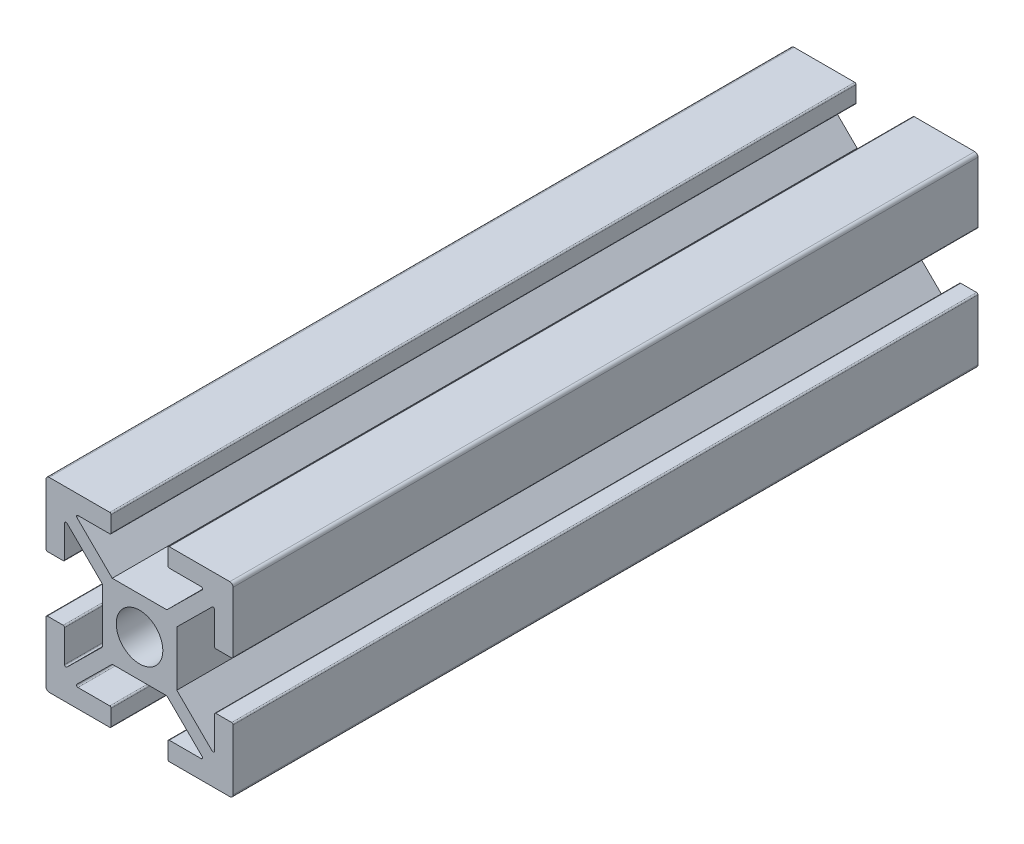
SolidWorks part; units mm, degrees
ref_plane "Front Plane" through (0, 0, 0) normal (0, 0, 1) x (1, 0, 0)
ref_plane "Top Plane" through (0, 0, 0) normal (0, 1, 0) x (1, 0, 0)
ref_plane "Right Plane" through (0, 0, 0) normal (1, 0, 0) x (0, 0, -1)
sketch "Sketch1" plane through (0, 0, 0) normal (0, 0, 1) x (1, 0, 0)
  line L0 (-31.3764, -0.0618) -> (-29.6764, -0.0618)
  line L1 (-24.6764, 6.9382) -> (-31.1764, 6.9382)
  line L2 (-31.5264, 0.0882) -> (-31.5264, 6.5882)
  line L3 (-18.5469, 0.9382) -> (-24.4133, 0.9382)
  line L4 (-25.4801, -6.0072) -> (-25.4801, -0.1164)
  line L5 (-29.5264, 0.0882) -> (-29.5264, 3.5244)
  line L6 (-28.0945, 4.9382) -> (-24.6764, 4.9382)
  line L7 (-24.5264, 5.0882) -> (-24.5264, 6.7882)
  line L8 (-29.5264, 4.9382) -> (-25.4801, 0.9382) construction
  line L9 (-29.271, 3.631) -> (-25.4801, -0.1164)
  line L10 (-28.1999, 4.6815) -> (-24.4133, 0.9382)
  line L11 (-13.4338, 4.9382) -> (-17.4801, 0.9382) construction
  line L12 (-21.4801, -3.0618) -> (-21.4801, 8.6268) construction
  line L13 (-21.4801, -3.0618) -> (-36.4642, -3.0618) construction
  line L14 (-14.7603, 4.6815) -> (-18.5469, 0.9382)
  line L15 (-13.6893, 3.631) -> (-17.4801, -0.1164)
  line L16 (-18.4338, 5.0882) -> (-18.4338, 6.7882)
  line L17 (-14.8657, 4.9382) -> (-18.2838, 4.9382)
  line L18 (-13.4338, 0.0882) -> (-13.4338, 3.5244)
  line L19 (-17.4801, -6.0072) -> (-17.4801, -0.1164)
  line L20 (-11.4338, 0.0882) -> (-11.4338, 6.5882)
  line L21 (-18.2838, 6.9382) -> (-11.7838, 6.9382)
  line L22 (-11.5838, -0.0618) -> (-13.2838, -0.0618)
  line L23 (-13.4338, -11.0618) -> (-17.4801, -7.0618) construction
  line L24 (-29.5264, -11.0618) -> (-25.4801, -7.0618) construction
  line L25 (-11.5838, -6.0618) -> (-13.2838, -6.0618)
  line L26 (-18.2838, -13.0618) -> (-11.7838, -13.0618)
  line L27 (-11.4338, -6.2118) -> (-11.4338, -12.7118)
  line L28 (-13.4338, -6.2118) -> (-13.4338, -9.648)
  line L29 (-14.8657, -11.0618) -> (-18.2838, -11.0618)
  line L30 (-18.4338, -11.2118) -> (-18.4338, -12.9118)
  line L31 (-13.6893, -9.7547) -> (-17.4801, -6.0072)
  line L32 (-14.7603, -10.8051) -> (-18.5469, -7.0618)
  line L33 (-28.1999, -10.8051) -> (-24.4133, -7.0618)
  line L34 (-29.271, -9.7547) -> (-25.4801, -6.0072)
  line L35 (-24.5264, -11.2118) -> (-24.5264, -12.9118)
  line L36 (-28.0945, -11.0618) -> (-24.6764, -11.0618)
  line L37 (-29.5264, -6.2118) -> (-29.5264, -9.648)
  line L38 (-18.5469, -7.0618) -> (-24.4133, -7.0618)
  line L39 (-31.5264, -6.2118) -> (-31.5264, -12.7118)
  line L40 (-24.6764, -13.0618) -> (-31.1764, -13.0618)
  line L41 (-31.3764, -6.0618) -> (-29.6764, -6.0618)
  circle A0 centre (-21.4801, -3.0618) radius 2.5
  arc A1 (-31.5264, 6.5882) -> (-31.1764, 6.9382) centre (-31.1764, 6.5882) cw
  arc A2 (-31.3764, -0.0618) -> (-31.5264, 0.0882) centre (-31.3764, 0.0882) cw
  arc A3 (-29.6764, -0.0618) -> (-29.5264, 0.0882) centre (-29.6764, 0.0882) ccw
  arc A4 (-24.6764, 6.9382) -> (-24.5264, 6.7882) centre (-24.6764, 6.7882) cw
  arc A5 (-24.6764, 4.9382) -> (-24.5264, 5.0882) centre (-24.6764, 5.0882) ccw
  arc A6 (-28.1999, 4.6815) -> (-28.0945, 4.9382) centre (-28.0945, 4.7882) cw
  arc A7 (-29.271, 3.631) -> (-29.5264, 3.5244) centre (-29.3764, 3.5244) ccw
  arc A8 (-13.6893, 3.631) -> (-13.4338, 3.5244) centre (-13.5838, 3.5244) cw
  arc A9 (-14.7603, 4.6815) -> (-14.8657, 4.9382) centre (-14.8657, 4.7882) ccw
  arc A10 (-18.2838, 4.9382) -> (-18.4338, 5.0882) centre (-18.2838, 5.0882) cw
  arc A11 (-18.2838, 6.9382) -> (-18.4338, 6.7882) centre (-18.2838, 6.7882) ccw
  arc A12 (-13.2838, -0.0618) -> (-13.4338, 0.0882) centre (-13.2838, 0.0882) cw
  arc A13 (-11.5838, -0.0618) -> (-11.4338, 0.0882) centre (-11.5838, 0.0882) ccw
  arc A14 (-11.4338, 6.5882) -> (-11.7838, 6.9382) centre (-11.7838, 6.5882) ccw
  arc A15 (-11.4338, -12.7118) -> (-11.7838, -13.0618) centre (-11.7838, -12.7118) cw
  arc A16 (-11.5838, -6.0618) -> (-11.4338, -6.2118) centre (-11.5838, -6.2118) cw
  arc A17 (-13.2838, -6.0618) -> (-13.4338, -6.2118) centre (-13.2838, -6.2118) ccw
  arc A18 (-18.2838, -13.0618) -> (-18.4338, -12.9118) centre (-18.2838, -12.9118) cw
  arc A19 (-18.2838, -11.0618) -> (-18.4338, -11.2118) centre (-18.2838, -11.2118) ccw
  arc A20 (-14.7603, -10.8051) -> (-14.8657, -11.0618) centre (-14.8657, -10.9118) cw
  arc A21 (-13.6893, -9.7547) -> (-13.4338, -9.648) centre (-13.5838, -9.648) ccw
  arc A22 (-29.271, -9.7547) -> (-29.5264, -9.648) centre (-29.3764, -9.648) cw
  arc A23 (-28.1999, -10.8051) -> (-28.0945, -11.0618) centre (-28.0945, -10.9118) ccw
  arc A24 (-24.6764, -11.0618) -> (-24.5264, -11.2118) centre (-24.6764, -11.2118) cw
  arc A25 (-24.6764, -13.0618) -> (-24.5264, -12.9118) centre (-24.6764, -12.9118) ccw
  arc A26 (-29.6764, -6.0618) -> (-29.5264, -6.2118) centre (-29.6764, -6.2118) cw
  arc A27 (-31.3764, -6.0618) -> (-31.5264, -6.2118) centre (-31.3764, -6.2118) ccw
  arc A28 (-31.5264, -12.7118) -> (-31.1764, -13.0618) centre (-31.1764, -12.7118) ccw
  point P27 (-18.4338, 4.9382)
  point P28 (-11.4338, -13.0618)
  point P47 (-17.4801, -3.0618)
  point P57 (-21.4801, 0.9382)
  point P59 (-18.4338, 6.9382)
  point P60 (-13.4338, -0.0618)
  point P61 (-11.4338, -0.0618)
  point P62 (-11.4338, 6.9382)
  point P112 (-25.4801, -3.0618)
  point P113 (-11.4338, -6.0618)
  point P114 (-13.4338, -6.0618)
  point P115 (-18.4338, -13.0618)
  point P116 (-21.4801, -7.0618)
  point P117 (-24.5264, -11.0618)
  point P118 (-24.5264, -13.0618)
  point P119 (-29.5264, -6.0618)
  point P120 (-18.4338, -11.0618)
  point P121 (-31.5264, -6.0618)
  point P122 (-31.5264, -13.0618)
  dimension "D3" = 0.35
  dimension "D4" = 0.15
  dimension "D5" = 0.15
  dimension "D6" = 0.15
  dimension "D7" = 0.15
  dimension "D8" = 0.15
  dimension "D9" = 0.15
  dimension "D1" = 0.75
  dimension "D2" = 0.75
extrude "Boss-Extrude1" add sketch "Sketch1" along normal blind 80
